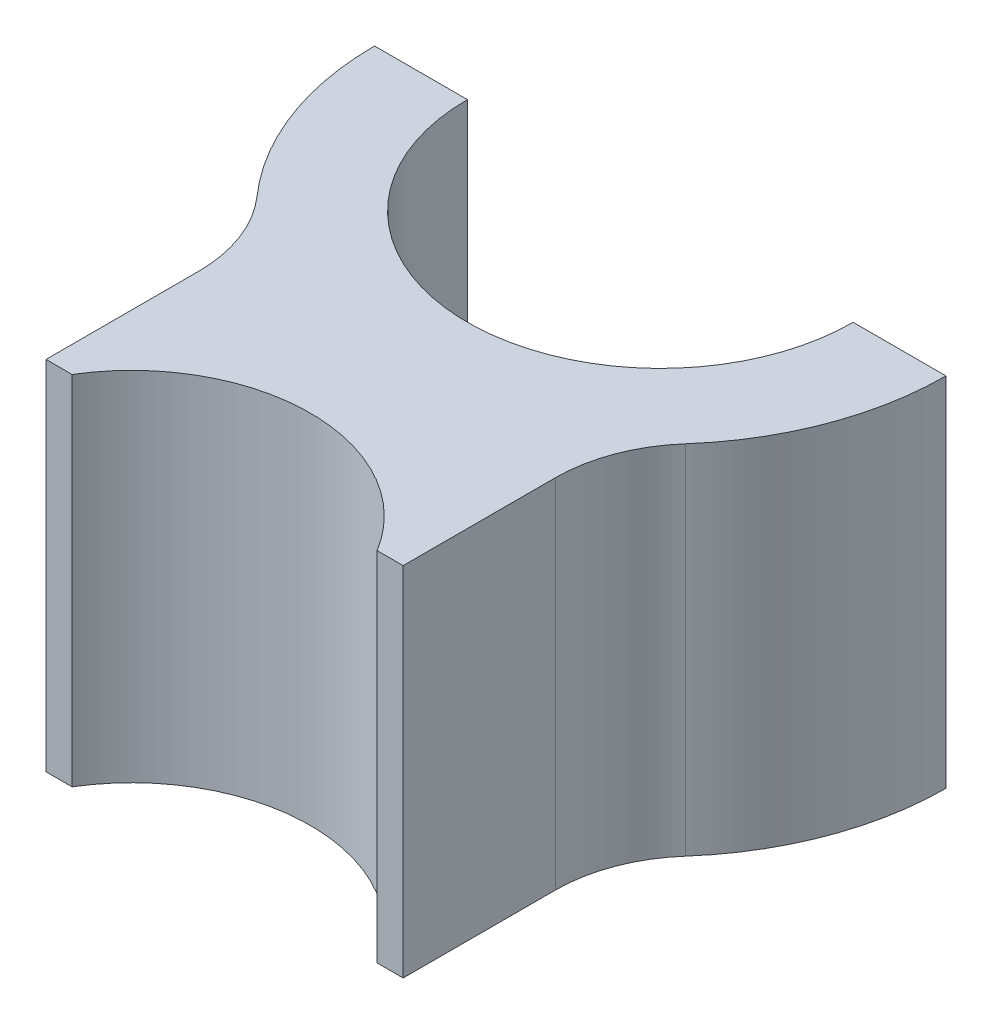
SolidWorks part; units mm, degrees
ref_plane "Спереди" through (0, 0, 0) normal (0, 0, 1) x (1, 0, 0)
ref_plane "Сверху" through (0, 0, 0) normal (0, 1, 0) x (1, 0, 0)
ref_plane "Справа" through (0, 0, 0) normal (1, 0, 0) x (0, 0, -1)
sketch "Эскиз1" plane through (0, 0, 0) normal (0, 1, 0) x (1, 0, 0)
  line L0 (-12.5, -37) -> (-12.5, -19.8431)
  line L1 (12.5, -37) -> (12.5, -19.8431)
  line L2 (-13.5, 0) -> (-20, 0)
  line L3 (13.5, 0) -> (20, 0)
  arc A0 (-20, 0) -> (-15, -13.2288) centre (0, 0) ccw
  arc A1 (-13.5, 0) -> (13.5, 0) centre (0, 0) ccw
  arc A2 (12.5, -37) -> (-12.5, -37) centre (0, -37) ccw
  arc A3 (15, -13.2288) -> (20, 0) centre (0, 0) ccw
  arc A4 (12.5, -19.8431) -> (15, -13.2288) centre (22.5, -19.8431) cw
  arc A5 (-12.5, -19.8431) -> (-15, -13.2288) centre (-22.5, -19.8431) ccw
  point P5 (12.5, -15.6125)
  dimension "D1" = 37
  dimension "D2" = 40
  dimension "D3" = 27
  dimension "D4" = 25
  dimension "D5" = 10
extrude "Бобышка-Вытянуть1" add sketch "Эскиз1" along normal blind 25
sketch "Эскиз2" plane through (0, 25, 0) normal (0, 1, 0) x (1, 0, 0)
  line L0 (-13.7482, -30.5) -> (14.8782, -30.5)
  line L1 (14.8782, -30.5) -> (14.8782, -40.5)
  line L2 (14.8782, -40.5) -> (-13.7482, -40.5)
  line L3 (-13.7482, -40.5) -> (-13.7482, -30.5)
  arc A0 (-13.5, 0) -> (13.5, 0) centre (0, 0) ccw construction
  point P4 (0, -13.5)
  dimension "D1" = 17
  dimension "D2" = 10
extrude "Вырез-Вытянуть1" cut sketch "Эскиз2" against normal through all
